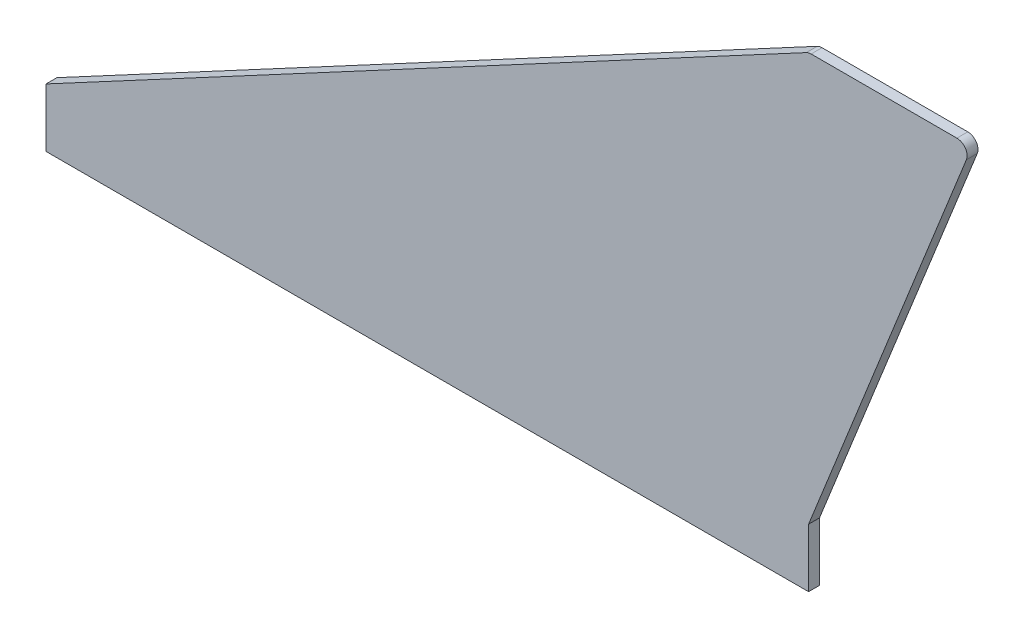
SolidWorks part; units mm, degrees
material "E-Glass Fiber"
ref_plane "Front Plane" through (0, 0, 0) normal (0, 0, 1) x (1, 0, 0)
ref_plane "Top Plane" through (0, 0, 0) normal (0, 1, 0) x (1, 0, 0)
ref_plane "Right Plane" through (0, 0, 0) normal (1, 0, 0) x (0, 0, -1)
sketch "Fin Profile" plane through (0, 0, 0) normal (0, 0, 1) x (1, 0, 0)
  line L0 (355.6, -27.2542) -> (0, -27.2542)
  line L1 (0, -27.2542) -> (0, 0)
  line L2 (0, 0) -> (355.6, 190.5)
  line L3 (355.6, 190.5) -> (431.8, 190.5)
  line L5 (431.8, 190.5) -> (355.6, 0)
  line L6 (355.6, 0) -> (355.6, -27.2542)
  dimension "D1" = 27.2542
  dimension "D2" = 355.6
  dimension "D3" = 76.2
  dimension "D4" = 355.6
  dimension "D5" = 190.5
extrude "Fin Body" add sketch "Fin Profile" along normal blind 5.08 contours L2 L3 L5 L6 L0 L1
fillet "Fin Fillets" radius 4.7625 2 edges at (431.8, 190.5, 2.54) (355.6, 190.5, 2.54)
equation "\"Root Chord\" = 14"
equation "\"Span\"= 7.5"
equation "\"Tip Chord\" = 3"
equation "\"Sweep Distance\" = 14"
equation "\"Fin Thickness\"= 0.2"
equation "\"Tab Height\"=1"
equation "\"D1@Fin Profile\"=\"Tab Height\" + (0.17/2) - (0.012)"
equation "\"D2@Fin Profile\" = \"Root Chord\""
equation "\"D3@Fin Profile\" = \"Tip Chord\""
equation "\"D4@Fin Profile\" = \"Sweep Distance\""
equation "\"D5@Fin Profile\" = \"Span\""
equation "\"Fillet Radius\"=0.1875"
equation "\"D1@Fin Fillets\" = \"Fillet Radius\""
equation "\"D1@Fin Body\"=\"Fin Thickness\""
